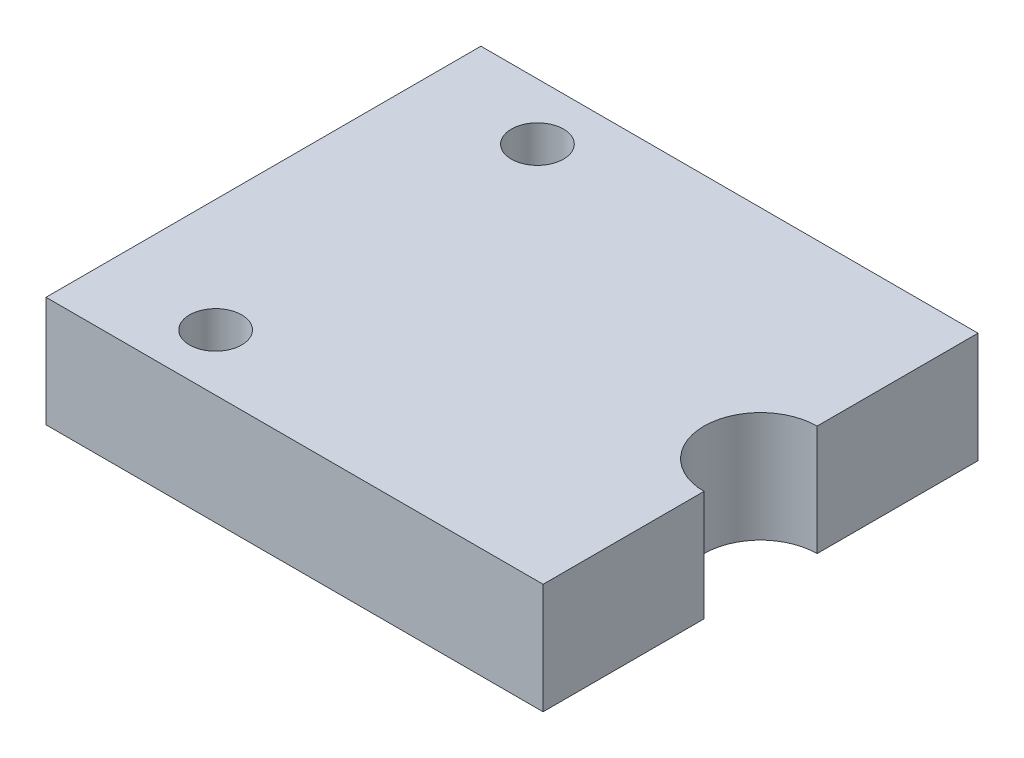
SolidWorks part; units mm, degrees
material "Aleación 6061"
ref_plane "Alzado" through (0, 0, 0) normal (0, 0, 1) x (1, 0, 0)
ref_plane "Planta" through (0, 0, 0) normal (0, 1, 0) x (1, 0, 0)
ref_plane "Vista lateral" through (0, 0, 0) normal (1, 0, 0) x (0, 0, -1)
sketch "Croquis2" plane through (0, 0, 0) normal (0, 1, 0) x (1, 0, 0)
  line L0 (0, 25) -> (-57.15, 25)
  line L4 (-57.15, 25) -> (-57.15, -25)
  line L8 (0, -25) -> (0, -6.5)
  line L9 (0, 6.5) -> (0, 25)
  line L11 (0, -25) -> (-57.15, -25)
  line L12 (0, 32.9631) -> (0, -34.8375) construction
  circle A0 centre (-44.15, -18.5) radius 3
  arc A2 (0, 6.5) -> (0, -6.5) centre (0, 0) ccw
  circle A5 centre (-44.15, 18.5) radius 3
  point P0 (0, 0)
  point P2 (0, 0)
  point P3 (0, 0)
  dimension "D3" = 25
  dimension "D4" = 6.5
  dimension "D6" = 6
  dimension "D7" = 6
  dimension "D9" = 13
  dimension "D1" = 50
  dimension "D2" = 57.15
extrude "Saliente-Extruir1" add sketch "Croquis2" along normal blind 12.7
